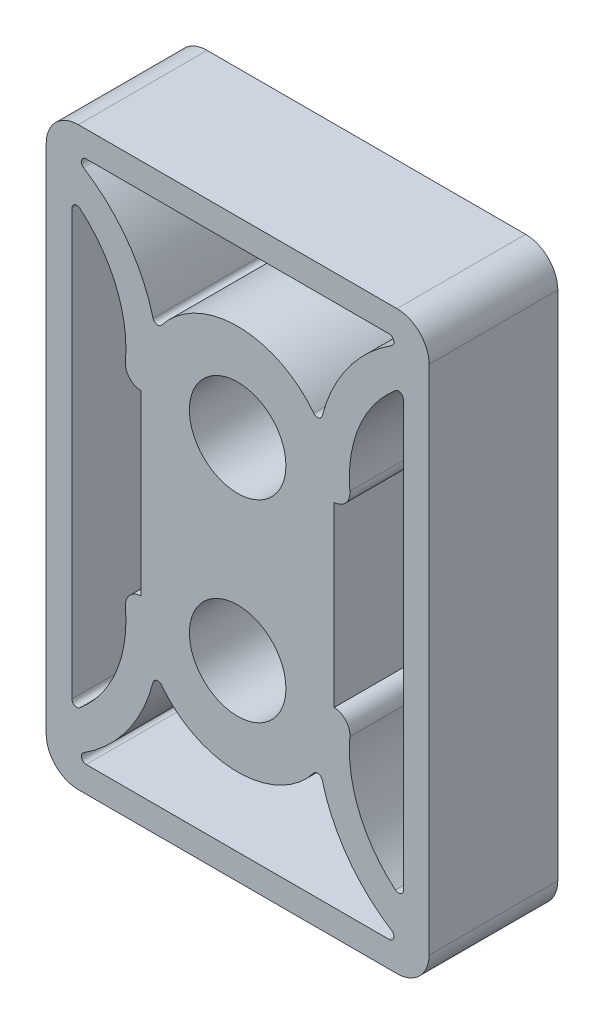
SolidWorks part; units mm, degrees
ref_plane "Front Plane" through (0, 0, 0) normal (0, 0, 1) x (1, 0, 0)
ref_plane "Top Plane" through (0, 0, 0) normal (0, 1, 0) x (1, 0, 0)
ref_plane "Right Plane" through (0, 0, 0) normal (1, 0, 0) x (0, 0, -1)
sketch "Sketch1" plane through (0, 0, 0) normal (0, 0, 1) x (1, 0, 0)
  line L0 (0, 3) -> (0, -3) construction
  line L1 (0, 3) -> (0, -3) construction
  line L2 (3, 3) -> (3, -3)
  line L3 (-3, 3) -> (-3, -3)
  circle A0 centre (0, 3) radius 1.5
  circle A1 centre (0, -3) radius 1.5
  arc A2 (3, 3) -> (-3, 3) centre (0, 3) ccw
  arc A3 (-3, -3) -> (3, -3) centre (0, -3) ccw
  point P2 (0, 0)
  point P7 (0, 0)
  dimension "D2" = 3
  dimension "D1" = 6
  dimension "D3" = 6
extrude "Boss-Extrude1" add sketch "Sketch1" along normal blind 4
sketch "Sketch3" plane through (0, 0, 0) normal (0, 0, 1) x (1, 0, 0)
  line L0 (-3, 3) -> (-3, -3) construction
  line L1 (3, -3) -> (3, 3) construction
  line L2 (-3, 3) -> (-3, -3) construction
  line L3 (3, -3) -> (3, 3) construction
  line L4 (0, 3) -> (0, -3) construction
  line L5 (-5.15, 8.15) -> (5.15, 8.15) construction
  line L6 (-5.15, 8.15) -> (-5.15, -8.15) construction
  line L7 (-5.15, -8.15) -> (5.15, -8.15) construction
  line L8 (5.15, 8.15) -> (5.15, -8.15) construction
  line L9 (-5.15, 8.15) -> (5.15, -8.15) construction
  line L10 (-5.15, -8.15) -> (5.15, 8.15) construction
  line L11 (-3, 0) -> (3, 0) construction
  line L12 (-5.95, 8.95) -> (-5.95, -8.95)
  line L13 (-5.95, -8.95) -> (5.95, -8.95)
  line L14 (5.95, 8.95) -> (5.95, -8.95)
  line L15 (-5.95, 8.95) -> (5.95, 8.95)
  line L16 (3, 2.7615) -> (3, 3)
  line L21 (3, -2.7615) -> (3, -3)
  line L24 (-3, -2.7615) -> (-3, -3)
  line L27 (-3, 2.7615) -> (-3, 3)
  line L28 (5.15, 6.911) -> (5.15, -6.911)
  line L29 (5.2847, -8.15) -> (-5.2847, -8.15)
  line L30 (-5.15, -6.911) -> (-5.15, 6.911)
  line L31 (-5.2847, 8.15) -> (5.2847, 8.15)
  arc A0 (-3, -3) -> (3, -3) centre (0, -3) ccw construction
  arc A1 (3, 3) -> (-3, 3) centre (0, 3) ccw construction
  arc A3 (-3, -3) -> (3, -3) centre (0, -3) ccw construction
  arc A5 (3, 3) -> (-3, 3) centre (0, 3) ccw construction
  arc A6 (2.9886, 3.2614) -> (7.65, 8.15) centre (7.4715, 3.6535) cw construction
  arc A7 (7.6698, 8.6496) -> (2.4905, 3.2178) centre (7.4715, 3.6535) ccw construction
  arc A8 (7.6302, 7.6504) -> (3.4867, 3.305) centre (7.4715, 3.6535) ccw construction
  arc A9 (7.6302, 7.6504) -> (7.6698, 8.6496) centre (7.65, 8.15) ccw construction
  arc A10 (2.4905, 3.2178) -> (3.4867, 3.305) centre (2.9886, 3.2614) ccw construction
  arc A11 (2.5562, 4.5703) -> (5.2847, 8.15) centre (7.4715, 3.6535) cw
  arc A16 (3.4867, 3.305) -> (5.15, 6.911) centre (7.4715, 3.6535) cw
  arc A17 (3.4867, 3.305) -> (3, 2.7615) centre (2.9886, 3.2614) cw
  arc A18 (2.5562, 4.5703) -> (3, 3) centre (0, 3) cw
  arc A19 (2.5562, -4.5703) -> (3, -3) centre (0, -3) ccw
  arc A20 (2.5562, -4.5703) -> (5.2847, -8.15) centre (7.4715, -3.6535) ccw
  arc A21 (3.4867, -3.305) -> (5.15, -6.911) centre (7.4715, -3.6535) ccw
  arc A22 (3.4867, -3.305) -> (3, -2.7615) centre (2.9886, -3.2614) ccw
  arc A23 (-2.5562, -4.5703) -> (-3, -3) centre (0, -3) cw
  arc A24 (-2.5562, -4.5703) -> (-5.2847, -8.15) centre (-7.4715, -3.6535) cw
  arc A25 (-3.4867, -3.305) -> (-5.15, -6.911) centre (-7.4715, -3.6535) cw
  arc A26 (-3.4867, -3.305) -> (-3, -2.7615) centre (-2.9886, -3.2614) cw
  arc A27 (-2.5562, 4.5703) -> (-3, 3) centre (0, 3) ccw
  arc A28 (-2.5562, 4.5703) -> (-5.2847, 8.15) centre (-7.4715, 3.6535) ccw
  arc A29 (-3.4867, 3.305) -> (-5.15, 6.911) centre (-7.4715, 3.6535) ccw
  arc A30 (-3.4867, 3.305) -> (-3, 2.7615) centre (-2.9886, 3.2614) ccw
  point P3 (0, 0)
  point P15 (4.2147, 6.759)
  dimension "D3" = 1
  dimension "D4" = 4
  dimension "D5" = 2.5
  dimension "D6" = 0.8
  dimension "D1" = 17.9
  dimension "D2" = 11.9
extrude "Boss-Extrude2" add sketch "Sketch3" along normal blind 4
fillet "Fillet1" radius 1 4 edges at (-5.95, 8.95, 2) (-5.95, -8.95, 2) (5.95, -8.95, 2) (5.95, 8.95, 2)
fillet "Fillet2" radius 0.15 12 edges at (5.15, -6.911, 2) (-5.15, -6.911, 2) (-5.15, 6.911, 2) (5.15, 6.911, 2) (-5.2847, 8.15, 2) (5.2847, 8.15, 2) (5.2847, -8.15, 2) (-5.2847, -8.15, 2) (2.5562, -4.5703, 2) (-2.5562, -4.5703, 2) (2.5562, 4.5703, 2) (-2.5562, 4.5703, 2)
